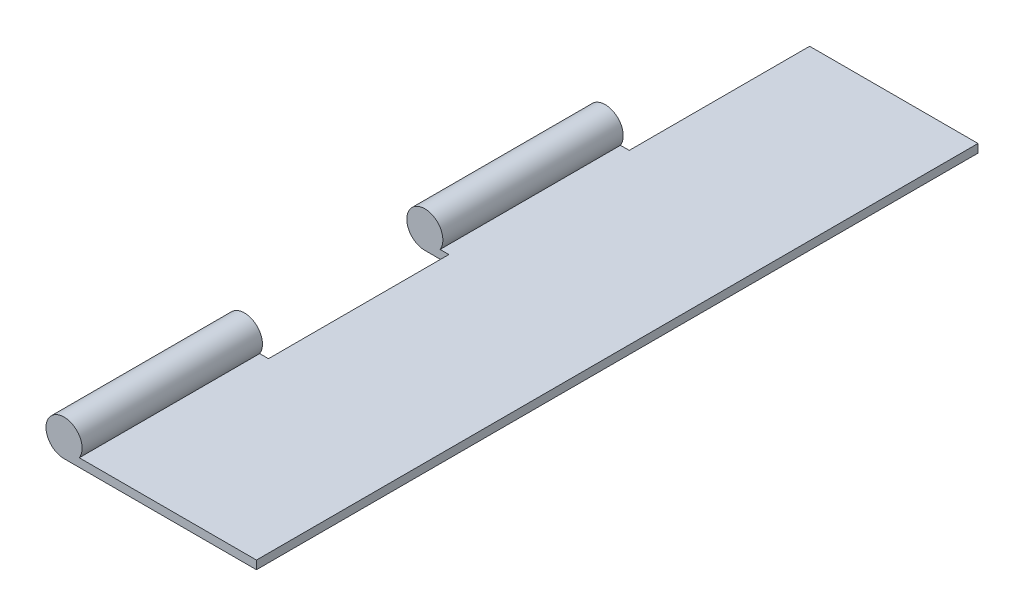
SolidWorks part; units mm, degrees
ref_plane "Plan de face" through (0, 0, 0) normal (0, 0, 1) x (1, 0, 0)
ref_plane "Plan de dessus" through (0, 0, 0) normal (0, 1, 0) x (1, 0, 0)
ref_plane "Plan de droite" through (0, 0, 0) normal (1, 0, 0) x (0, 0, -1)
sketch "Esquisse1" plane through (0, 0, 0) normal (0, 0, 1) x (1, 0, 0)
  line L1 (0, 0) -> (16, 0)
  line L3 (1.2689, 0.7) -> (16, 0.7)
  line L4 (16, 0) -> (16, 0.7)
  arc A0 (1.2689, 0.7) -> (0, 0) centre (0, 1.5) ccw
  dimension "D1" = 16
  dimension "D2" = 3
  dimension "D3" = 0.7
extrude "Extrusion1" add sketch "Esquisse1" along normal blind 60
sketch "Esquisse2" plane through (0, 0.7, 0) normal (0, 1, 0) x (1, 0, 0)
  line L1 (16, -60) -> (16, 0) construction
  line L2 (2, -45) -> (-5.047, -45)
  line L3 (2, -45) -> (2, -30)
  line L4 (2, -30) -> (-5.047, -30)
  line L5 (-5.047, -45) -> (-5.047, -30)
  line L7 (16, -60) -> (1.2689, -60) construction
  dimension "D1" = 14
  dimension "D2" = 15
  dimension "D3" = 15
extrude "Extrusion2" cut sketch "Esquisse2" along normal through all from offset 10
pattern_linear "Répétition linéaire1" count 2 spacing 30 along (0, 0, -1) of "Extrusion2"
